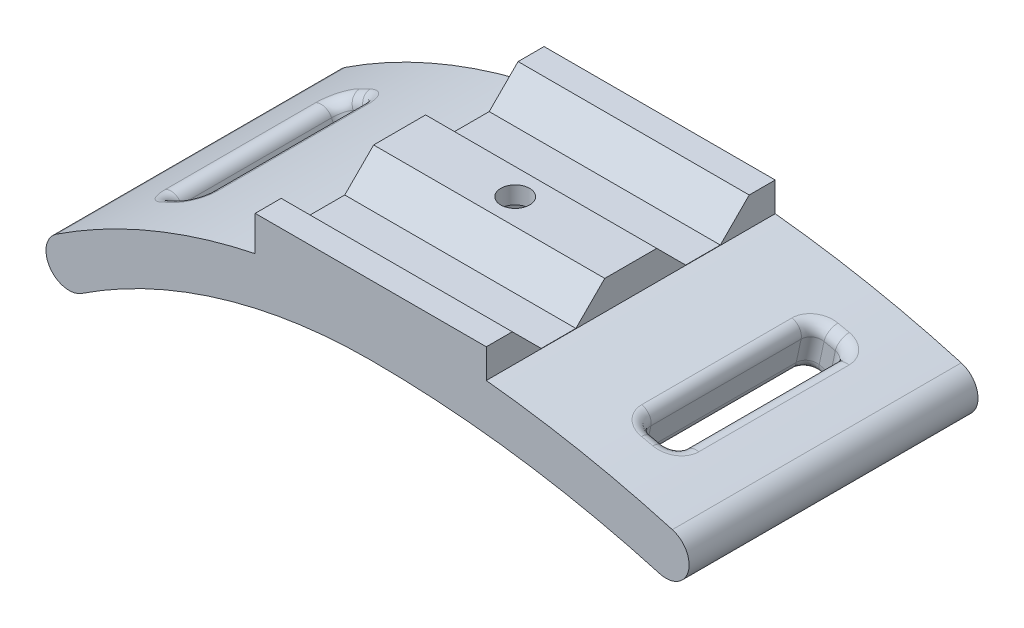
SolidWorks part; units mm, degrees
ref_plane "Top Plane" through (0, 0, 0) normal (0, 0, 1) x (1, 0, 0)
ref_plane "Right Plane" through (0, 0, 0) normal (0, 1, 0) x (1, 0, 0)
ref_plane "Front Plane" through (0, 0, 0) normal (1, 0, 0) x (0, 0, -1)
sketch "Sketch1" plane through (0, 0, 0) normal (0, 0, 1) x (1, 0, 0)
  line L0 (0, 23) -> (0, 15) construction
  line L1 (-50, 0) -> (50, 0) construction
  line L2 (-50, 0) -> (-50, 23) construction
  line L3 (-50, 23) -> (50, 23) construction
  line L4 (50, 0) -> (50, 23) construction
  line L5 (0, 23) -> (0, 27) construction
  line L6 (-20, 27) -> (20, 27)
  line L7 (-20, 27) -> (-20, 20.9552)
  line L9 (20, 27) -> (20, 21.9448)
  arc A0 (-50, 0) -> (0, 15) centre (0, -75.8333) cw
  arc A1 (-54.4037, 6.6789) -> (0, 23) centre (0, -75.8333) cw construction
  arc A2 (-54.4037, 6.6789) -> (-50, 0) centre (-52.2018, 3.3394) ccw
  arc A4 (-54.4037, 6.6789) -> (-20, 20.9552) centre (0, -75.8333) cw
  arc A6 (0, 15) -> (50, 8) centre (0, -167.0714) cw
  arc A7 (50, 8) -> (52.1969, 15.6924) centre (51.0985, 11.8462) ccw
  arc A8 (52.1969, 15.6924) -> (20, 21.9448) centre (0, -167.0714) ccw
  point P22 (20, 20.9552)
  point P23 (52.5979, 13.5637)
  point P24 (0, 0)
  dimension "D2" = 8
  dimension "D1" = 100
  dimension "D3" = 15
  dimension "D4" = 12
  dimension "D5" = 40
  dimension "D6" = 8
extrude "Boss-Extrude1" add sketch "Sketch1" along normal mid plane 50
sketch "Sketch3" plane through (0, 27, 0) normal (0, 1, 0) x (1, 0, 0)
  circle A0 centre (0, 0) radius 2.5
  dimension "D1" = 5
extrude "Cut-Extrude1" cut sketch "Sketch3" against normal blind 50
sketch "Sketch4" plane through (0, 27, 0) normal (0, 1, 0) x (1, 0, 0)
  line L0 (-4.3301, 0) -> (-2.1651, -3.75)
  line L1 (-2.1651, -3.75) -> (2.1651, -3.75)
  line L2 (2.1651, -3.75) -> (4.3301, 0)
  line L3 (4.3301, 0) -> (2.1651, 3.75)
  line L4 (2.1651, 3.75) -> (-2.1651, 3.75)
  line L5 (-2.1651, 3.75) -> (-4.3301, 0)
  circle A0 centre (0, 0) radius 4.3301 construction
  dimension "D1" = 7.5
extrude "Cut-Extrude2" cut sketch "Sketch4" against normal through all from offset 3 offset against normal yes
sketch "Sketch5" plane through (-20, 0, 0) normal (-1, 0, 0) x (0, 0, 1)
  line L0 (20.5, 27) -> (15.5, 22)
  line L1 (25, 27) -> (-25, 27) construction
  line L2 (15.5, 22) -> (9.5, 22)
  line L3 (9.5, 22) -> (4.5, 27)
  line L4 (12.5, 22) -> (12.5, 27) construction
  line L5 (0, 0) -> (25, 0) construction
  line L6 (25, 0) -> (12.5, 22) construction
  line L7 (12.5, 22) -> (12.5, 0) construction
  line L8 (20.5, 27) -> (4.5, 27)
  dimension "D1" = 6
  dimension "D2" = 135
  dimension "D3" = 5
extrude "Cut-Extrude3" cut sketch "Sketch5" against normal through all
mirror "Mirror1" about plane through (0, 0, 0) normal (0, 0, 1) of "Cut-Extrude3"
sketch "Sketch6" plane through (0, 0, 25) normal (0, 0, 1) x (1, 0, 0)
  line L0 (36.9141, 19.4051) -> (42.7808, 18.1472)
  line L1 (-45.7043, 11.8488) -> (-40.302, 14.4594)
  line L2 (-45.7043, 11.8488) -> (-42.2018, 4.6011)
  line L3 (-42.2018, 4.6011) -> (-36.7996, 7.2118)
  line L4 (-40.302, 14.4594) -> (-36.7996, 7.2118)
  line L5 (36.9141, 19.4051) -> (35.2318, 11.5587)
  line L6 (35.2318, 11.5587) -> (41.0985, 10.3008)
  line L7 (42.7808, 18.1472) -> (41.0985, 10.3008)
  arc A1 (52.1969, 15.6924) -> (20, 21.9448) centre (0, -167.0714) ccw construction
  arc A2 (0, 15) -> (-50, 0) centre (0, -75.8333) ccw construction
  arc A3 (-20, 20.9552) -> (-54.4037, 6.6789) centre (0, -75.8333) ccw construction
  arc A4 (-54.4037, 6.6789) -> (-50, 0) centre (-52.2018, 3.3394) ccw construction
  arc A6 (50, 8) -> (0, 15) centre (0, -167.0714) ccw construction
  point P20 (-43.0031, 13.1541)
  point P21 (-52.2018, 3.3394)
  point P25 (39.8475, 18.7762)
  point P31 (51.0985, 11.8462)
  dimension "D1" = 6
  dimension "D2" = 10
  dimension "D3" = 6
  dimension "D4" = 10
extrude "Cut-Extrude4" cut sketch "Sketch6" against normal offset from surface (30 mm away) 10 from offset 10 up to face at (-0.3445, 16.3014, -25) offset against normal yes
fillet "Fillet1" radius 2 24 edges at (-43.0031, 13.1541, -15) (-39.5223, 5.951, -15) (-39.5223, 5.951, 15) (-43.0031, 13.1541, 15) (-45.6844, 11.8078, 0) (-43.9431, 8.2044, -15) (-42.2018, 4.6011, 0) (-43.9431, 8.2044, 15) (-40.2822, 14.4184, 0) (-38.5409, 10.8151, 15) (-36.7996, 7.2118, 0) (-38.5409, 10.8151, -15) (39.8475, 18.7762, -15) (38.1703, 10.9539, -15) (38.1703, 10.9539, 15) (39.8475, 18.7762, 15) (36.9092, 19.3819, 0) (36.0705, 15.4703, -15) (35.2318, 11.5587, 0) (36.0705, 15.4703, 15) (42.7758, 18.1241, 0) (41.9372, 14.2125, 15) (41.0985, 10.3008, 0) (41.9372, 14.2125, -15)
